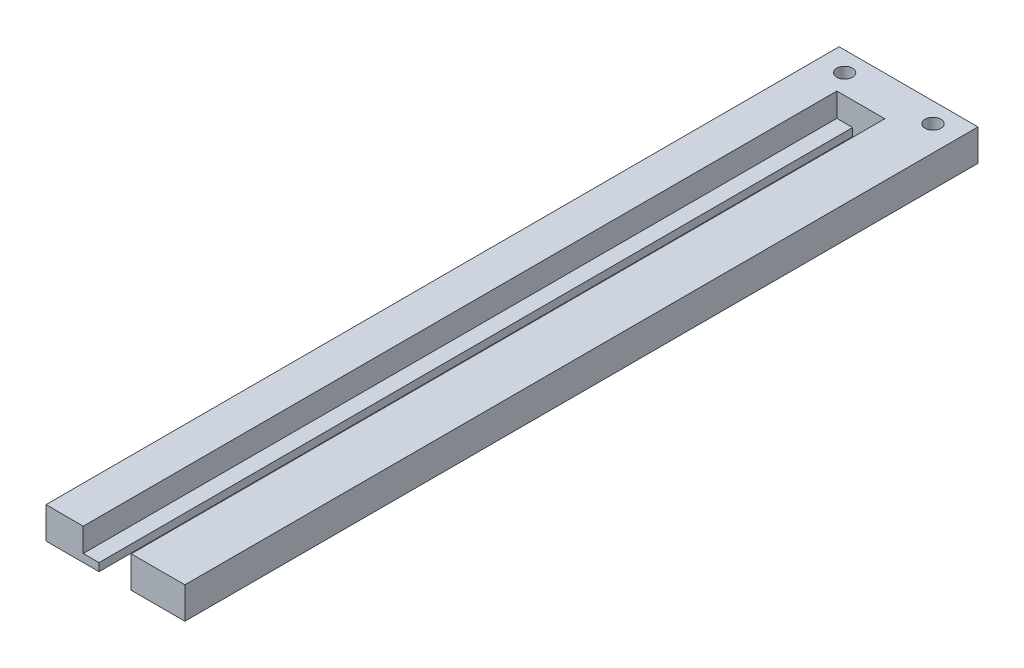
SolidWorks part; units mm, degrees
ref_plane "Front Plane" through (0, 0, 0) normal (0, 0, 1) x (1, 0, 0)
ref_plane "Top Plane" through (0, 0, 0) normal (0, 1, 0) x (1, 0, 0)
ref_plane "Right Plane" through (0, 0, 0) normal (1, 0, 0) x (0, 0, -1)
sketch "Sketch1" plane through (0, 0, 0) normal (0, 0, 1) x (1, 0, 0)
  line L1 (-13.97, -3.175) -> (13.97, -3.175)
  line L2 (-13.97, -3.175) -> (-13.97, 3.175)
  line L3 (-13.97, 3.175) -> (13.97, 3.175)
  line L4 (13.97, -3.175) -> (13.97, 3.175)
  line L5 (-13.97, -3.175) -> (13.97, 3.175) construction
  line L6 (-13.97, 3.175) -> (13.97, -3.175) construction
  point P0 (0, 0)
  dimension "D1" = 27.94
  dimension "D2" = 6.35
extrude "Boss-Extrude1" add sketch "Sketch1" along normal blind 7.9502
sketch "Sketch2" plane through (0, 0, 7.9502) normal (0, 0, 1) x (1, 0, 0)
  line L0 (-3.302, -3.175) -> (-3.302, -1.5875)
  line L1 (-13.97, -3.175) -> (13.97, -3.175) construction
  line L2 (-3.302, -1.5875) -> (-6.477, -1.5875)
  line L3 (-6.477, -1.5875) -> (-6.477, 3.175)
  line L4 (13.97, 3.175) -> (-13.97, 3.175) construction
  line L5 (-6.477, 3.175) -> (-13.97, 3.175)
  line L6 (-13.97, 3.175) -> (-13.97, -3.175)
  line L7 (-13.97, -3.175) -> (-3.302, -3.175)
  line L9 (13.97, -3.175) -> (3.175, -3.175)
  line L10 (13.97, -3.175) -> (13.97, 3.175)
  line L11 (13.97, 3.175) -> (3.175, 3.175)
  line L12 (3.175, -3.175) -> (3.175, 3.175)
  dimension "D1" = 1.5875
  dimension "D2" = 3.302
  dimension "D3" = 3.175
  dimension "D4" = 3.175
extrude "Boss-Extrude2" add sketch "Sketch2" along normal blind 151.6062
sketch "Sketch4" plane through (0, 3.175, 0) normal (0, 1, 0) x (1, 0, 0)
  line L0 (13.97, 0) -> (-13.97, 0) construction
  line L1 (-13.97, -159.5564) -> (-13.97, 0) construction
  line L2 (13.97, -159.5564) -> (13.97, 0) construction
  circle A0 centre (-8.89, -3.9751) radius 1.5875
  circle A1 centre (8.89, -3.9751) radius 1.5875
  dimension "D1" = 3.175
  dimension "D2" = 3.9751
  dimension "D3" = 3.9751
  dimension "D4" = 5.08
  dimension "D5" = 5.08
extrude "Cut-Extrude1" cut sketch "Sketch4" against normal through all
